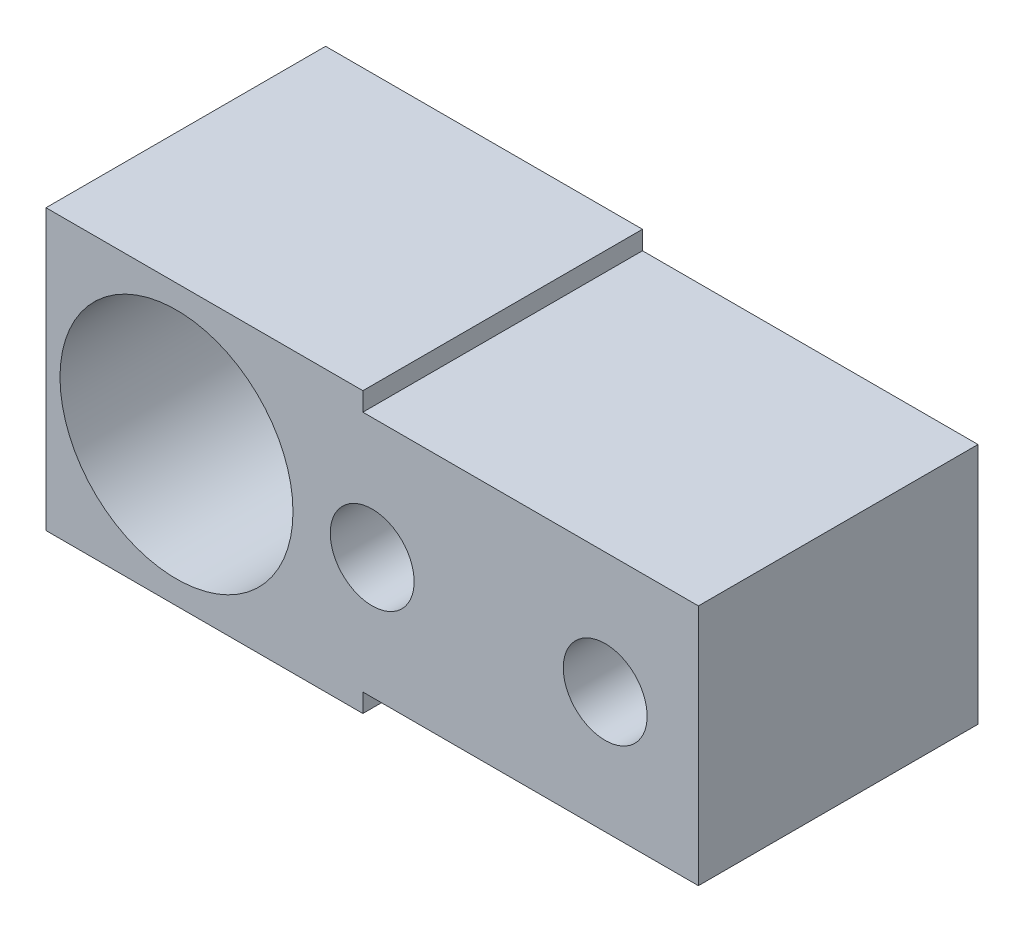
SolidWorks part; units mm, degrees
material "3.1645 (AlCuMgPb) eloxiert"
ref_plane "Vorne" through (0, 0, 0) normal (0, 0, 1) x (1, 0, 0)
ref_plane "Oben" through (0, 0, 0) normal (0, 1, 0) x (1, 0, 0)
ref_plane "Rechts" through (0, 0, 0) normal (1, 0, 0) x (0, 0, -1)
sketch "Skizze1" plane through (0, 0, 0) normal (0, 0, 1) x (1, 0, 0)
  line L0 (34, 15) -> (34, 13)
  line L1 (0, -15) -> (34, -15)
  line L2 (0, -15) -> (0, 15)
  line L3 (0, 15) -> (34, 15)
  line L4 (70, -13) -> (70, 13)
  line L5 (34, 13) -> (70, 13)
  line L6 (70, -13) -> (34, -13)
  line L7 (34, -13) -> (34, -15)
  point P4 (0, 0)
  dimension "D1" = 30
  dimension "D2" = 70
  dimension "D3" = 34
  dimension "D4" = 2
extrude "Aufsatz-Linear austragen1" add sketch "Skizze1" along normal blind 30
sketch "Skizze6" plane through (0, 0, 30) normal (0, 0, 1) x (1, 0, 0)
  line L0 (0, 15) -> (0, -15) construction
  circle A0 centre (14, 0) radius 12.5
  dimension "D1" = 14
  dimension "D2" = 25
extrude "Schnitt-Linear austragen1" cut sketch "Skizze6" against normal blind 20
hole_wizard "M16 Gewindebohrung1" positions "Skizze9" profile "Skizze8" tap size "M16" standard "Gabler-Normteile"
sketch "Skizze9" plane through (0, 0, 0) normal (0, 0, -1) x (-1, 0, 0)
  point P0 (-14, 0)
  dimension "D1" = 14
sketch "Skizze8" plane through (14, 0, 0) normal (1, 0, 0) x (0, 1, 0)
  line L0 (0, 0) -> (0, 46.206)
  line L1 (0, 46.206) -> (7, 42)
  line L2 (7, 42) -> (7, 0)
  line L5 (7, 0) -> (0, 0)
  line L10 (0, 46.206) -> (-7, 42) construction
  line L11 (0, -6.35) -> (0, 107.95) construction
  dimension "Bohrerdurchmesser" = 14
  dimension "Bohrungstiefe" = 42
  dimension "Spitzenwinkel" = 118
cosmetic thread "Bohrungsgewinde1" parameters "D1"=10, "D2"=16
hole_wizard "Stirnsenkung für M8 Zylinderschraube mit Innensechskant1" positions "Skizze11" profile "Skizze10" counterbore size "M8" standard "Gabler-Normteile" end condition through all
sketch "Skizze11" plane through (0, 0, 0) normal (0, 0, -1) x (-1, 0, 0)
  line L0 (-70, -13) -> (-70, 13) construction
  point P0 (-60, 0)
  point P2 (-35, 0)
  point P5 (-70, 0)
  dimension "D1" = 10
  dimension "D2" = 25
sketch "Skizze10" plane through (60, 0, 0) normal (1, 0, 0) x (0, 1, 0)
  line L0 (0, 0) -> (0, 30)
  line L1 (0, 30) -> (4.5, 30)
  line L3 (4.5, 30) -> (4.5, 8.6)
  line L4 (4.5, 8.6) -> (7.5, 8.6)
  line L5 (7.5, 8.6) -> (7.5, 0)
  line L7 (7.5, 0) -> (0, 0)
  line L11 (0, -6.35) -> (0, 107.95) construction
  dimension "Bohrerdurchmesser" = 9
  dimension "Bohrungstiefe" = 30
  dimension "Senkdurchmesser2" = 15
  dimension "Senktiefe2" = 8.6
chamfer "Fase1" distance 0.5 angle 45 1 edges at (21, 0, 10)
